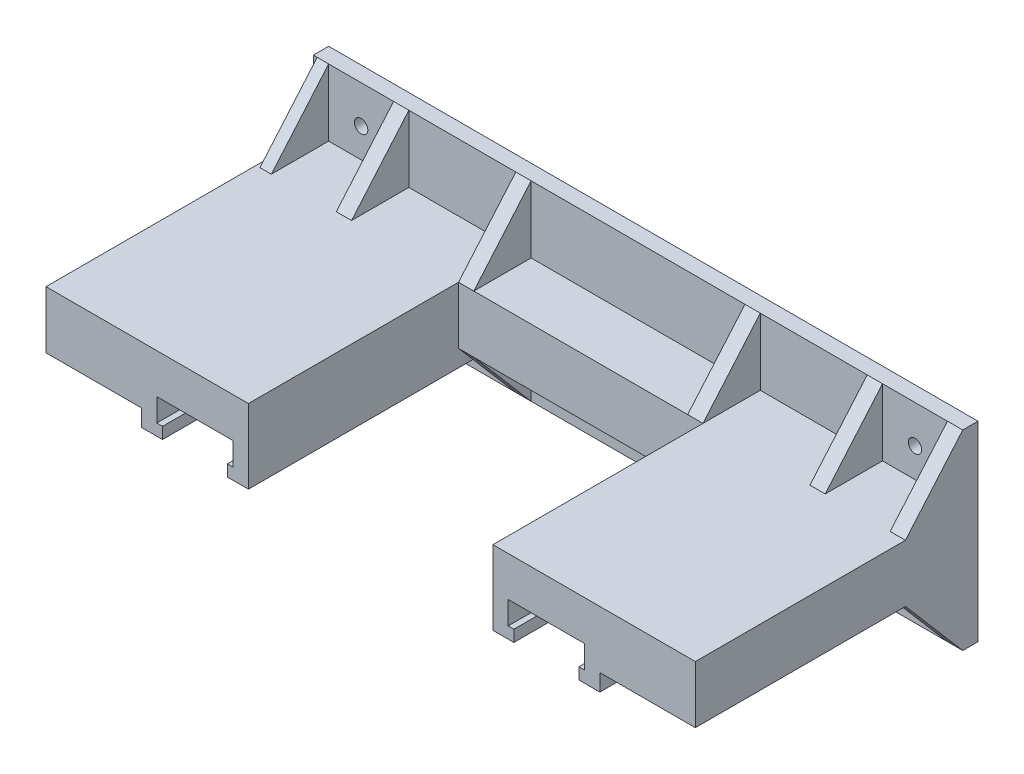
SolidWorks part; units mm, degrees
ref_plane "Alzado" through (0, 0, 0) normal (0, 0, 1) x (1, 0, 0)
ref_plane "Planta" through (0, 0, 0) normal (0, 1, 0) x (1, 0, 0)
ref_plane "Vista lateral" through (0, 0, 0) normal (1, 0, 0) x (0, 0, -1)
sketch "Croquis1" plane through (0, 0, 0) normal (0, 0, 1) x (1, 0, 0)
  line L1 (-85, 25) -> (85, 25)
  line L2 (-85, 25) -> (-85, -25)
  line L3 (-85, -25) -> (85, -25)
  line L4 (85, 25) -> (85, -25)
  line L5 (-85, 25) -> (85, -25) construction
  line L6 (-85, -25) -> (85, 25) construction
  point P0 (0, 0)
  dimension "D1" = 170
  dimension "D2" = 50
extrude "Saliente-Extruir1" add sketch "Croquis1" along normal blind 4
sketch "Croquis3" plane through (0, 0, 4) normal (0, 0, 1) x (1, 0, 0)
  line L0 (-85, 25) -> (-85, -25) construction
  line L2 (-85, 7.5) -> (85, 7.5)
  line L4 (-60, -11.9212) -> (-56, -11.9212)
  line L6 (-60, -7.5) -> (-85, -7.5)
  line L7 (-47.748, 25) -> (-47.748, 7.5) construction
  line L8 (85, 25) -> (-85, 25) construction
  line L9 (-47.748, 7.5) -> (-47.748, 25) construction
  line L10 (-56, -2.9212) -> (-56, -8.9212)
  line L11 (-85, -25) -> (85, -25) construction
  line L13 (-60, -7.5) -> (-60, -11.9212)
  line L17 (-32, -11.9212) -> (-32, -7.5)
  line L19 (32, -7.5) -> (32, -11.9212)
  line L22 (-36, -11.9212) -> (-32, -11.9212)
  line L23 (32, -11.9212) -> (36, -11.9212)
  line L26 (56, -11.9212) -> (60, -11.9212)
  line L27 (60, -11.9212) -> (60, -7.5)
  line L30 (0, 25) -> (0, -25) construction
  line L31 (-56, -8.9212) -> (-54.5, -8.9212)
  line L32 (-54.5, -8.9212) -> (-54.5, -11.9212)
  line L33 (-54.5, -11.9212) -> (-56, -11.9212)
  line L34 (-36, -8.9212) -> (-37.5, -8.9212)
  line L35 (-37.5, -8.9212) -> (-37.5, -11.9212)
  line L36 (-37.5, -11.9212) -> (-36, -11.9212)
  line L37 (37.5, -11.9212) -> (36, -11.9212)
  line L38 (37.5, -8.9212) -> (37.5, -11.9212)
  line L39 (36, -8.9212) -> (37.5, -8.9212)
  line L40 (56, -8.9212) -> (54.5, -8.9212)
  line L41 (54.5, -11.9212) -> (56, -11.9212)
  line L42 (54.5, -8.9212) -> (54.5, -11.9212)
  line L43 (85, -7.5) -> (60, -7.5)
  line L46 (85, 7.5) -> (85, -7.5)
  line L47 (-85, 7.5) -> (-85, -7.5)
  line L49 (-56, -2.9212) -> (-36, -2.9212)
  line L52 (56, -2.9212) -> (36, -2.9212)
  line L54 (32, -7.5) -> (-32, -7.5)
  line L55 (-36, -2.9212) -> (-36, -8.9212)
  line L56 (36, -2.9212) -> (36, -8.9212)
  line L57 (56, -2.9212) -> (56, -8.9212)
  line L58 (-85, 0) -> (85, 0) construction
  point P50 (0, -10.136)
  dimension "D1" = 4
  dimension "D2" = 3
  dimension "D3" = 6
  dimension "D4" = 1.5
  dimension "D5" = 15
  dimension "D6" = 20
  dimension "D7" = 25
extrude "Saliente-Extruir2" add sketch "Croquis3" along normal blind 70
sketch "Croquis4" plane through (-85, 0, 0) normal (-1, 0, 0) x (0, 0, 1)
  line L0 (4, -25) -> (19, -7.5)
  line L1 (74, -7.5) -> (4, -7.5) construction
  line L2 (19, -7.5) -> (4, -7.5)
  line L3 (4, -7.5) -> (4, -25)
  line L4 (0, 0) -> (74, 0) construction
  line L5 (74, 7.5) -> (74, -7.5) construction
  dimension "D1" = 15
extrude "Saliente-Extruir3" add sketch "Croquis4" against normal blind 25
sketch "Croquis5" plane through (32, 0, 0) normal (-1, 0, 0) x (0, 0, 1)
  line L0 (19, -7.5) -> (4, -25)
  line L1 (4, -25) -> (4, -7.5)
  line L2 (4, -7.5) -> (19, -7.5)
extrude "Saliente-Extruir4" add sketch "Croquis5" along normal up to surface (64 mm away) up to face at (-32, -9.7106, 39)
ref_plane "Plano1" through (60, -11.9212, 4) normal (0, 0, -1) x (-1, 0, 0)
sketch "Croquis7" plane through (60, 0, 0) normal (1, 0, 0) x (0, 0, -1)
  line L0 (-4, -25) -> (-19, -7.5)
  line L1 (-4, -31.1712) -> (-4, 7.3288) construction
  line L2 (-4, -25) -> (-15.2104, -11.9212) construction
  line L3 (-74, -7.5) -> (-4, -7.5) construction
  line L4 (-19, -7.5) -> (-4, -7.5)
  line L5 (-74, -7.5) -> (-4, -7.5) construction
  line L6 (-4, -7.5) -> (-4, -25)
  dimension "D1" = 15
extrude "Saliente-Extruir5" add sketch "Croquis7" along normal blind 25
sketch "Croquis9" plane through (0, 0, 74) normal (0, 0, 1) x (1, 0, 0)
  line L0 (-60, -7.5) -> (-85, -7.5) construction
  line L1 (-81, -7.5) -> (-64, -7.5)
  line L2 (-81, -7.5) -> (-81, -25)
  line L3 (-81, -25) -> (-64, -25)
  line L4 (-64, -7.5) -> (-64, -25)
  line L5 (-85, -25) -> (-60, -25) construction
  line L6 (-32, -7.5) -> (32, -7.5) construction
  line L8 (-28, -7.5) -> (-28, -25)
  line L11 (-32, -25) -> (32, -25) construction
  line L12 (60, -7.5) -> (85, -7.5) construction
  line L16 (28, -7.5) -> (28, -25)
  line L17 (64, -7.5) -> (81, -7.5)
  line L18 (64, -7.5) -> (64, -25)
  line L19 (64, -25) -> (81, -25)
  line L20 (81, -7.5) -> (81, -25)
  line L21 (85, -25) -> (60, -25) construction
  line L22 (-81, -14.0076) -> (-85, -14.0076) construction
  line L23 (-85, -25) -> (-85, -7.5) construction
  line L24 (-64, -17.5204) -> (-60, -17.5204) construction
  line L25 (-60, -11.9212) -> (-60, -25) construction
  line L26 (-32, -20.3836) -> (-28, -20.3836) construction
  line L27 (-32, -25) -> (-32, -11.9212) construction
  line L28 (-28, -7.5) -> (28, -7.5)
  line L29 (28, -15.1674) -> (32, -15.1674) construction
  line L30 (32, -11.9212) -> (32, -25) construction
  line L31 (60, -17.5204) -> (64, -17.5204) construction
  line L32 (60, -25) -> (60, -11.9212) construction
  line L33 (81, -12.1629) -> (85, -12.1629) construction
  line L34 (85, -7.5) -> (85, -25) construction
  line L35 (-28, -25) -> (28, -25)
  dimension "D1" = 4
extrude "Cortar-Extruir1" cut sketch "Croquis9" against normal blind 70
sketch "Croquis11" plane through (0, -7.5, 0) normal (0, -1, 0) x (1, 0, 0)
  line L0 (32, 74) -> (32, 15.2104) construction
  line L1 (-32, 74) -> (32, 74)
  line L2 (-32, 74) -> (-32, 19)
  line L3 (-32, 19) -> (32, 19)
  line L4 (32, 74) -> (32, 19)
  line L5 (-32, 19) -> (-28, 19) construction
extrude "Cortar-Extruir4" cut sketch "Croquis11" against normal blind 15
sketch "Croquis12" plane through (0, 0, 4) normal (0, 0, 1) x (1, 0, 0)
  line L0 (-72.5, 15.1385) -> (-74.25, 15.1385) construction
  line L1 (-72.5, 15.1385) -> (-70.75, 15.1385) construction
  line L2 (-72.5, 15.1385) -> (-72.5, 16.8885) construction
  line L4 (-72.5, 15.1385) -> (-72.5, -7.5) construction
  line L5 (-64, -7.5) -> (-81, -7.5) construction
  line L6 (-85, 0) -> (0, 0) construction
  line L7 (-85, 7.5) -> (-85, -7.5) construction
  line L8 (0, 0) -> (0, 13.3885) construction
  line L9 (0, 15.1385) -> (72.5, 15.1385) construction
  line L10 (-72.5, -15.1385) -> (72.5, -15.1385) construction
  circle A0 centre (-72.5, 15.1385) radius 1.75
  circle A1 centre (-72.5, -15.1385) radius 1.75
  circle A2 centre (72.5, -15.1385) radius 1.75
  circle A3 centre (72.5, 15.1385) radius 1.75
  dimension "D1" = 3.5
extrude "Cortar-Extruir5" cut sketch "Croquis12" against normal blind 15
sketch "Croquis14" plane through (-85, 0, 0) normal (-1, 0, 0) x (0, 0, 1)
  line L0 (19, -7.5) -> (4, -7.5)
  line L1 (4, 4.2459) -> (4, -28.0883) construction
  line L2 (4, -7.5) -> (4, -25)
  line L3 (4, -25) -> (19, -7.5)
extrude "Cortar-Extruir6" cut sketch "Croquis14" against normal blind 1
sketch "Croquis15" plane through (0, 0, 19) normal (0, 0, 1) x (1, 0, 0)
  line L0 (-32, 0) -> (32, 0)
  line L1 (32, 7.5) -> (32, -7.5) construction
  point P7 (0, 0)
ref_plane "Plano3" through (0, 0, 0) normal (0, -1, 0) x (1, 0, 0)
mirror "Simetría1" about plane through (0, 0, 0) normal (0, -1, 0) of "Cortar-Extruir1", "Saliente-Extruir5", "Saliente-Extruir4", "Saliente-Extruir3", "Cortar-Extruir6"
